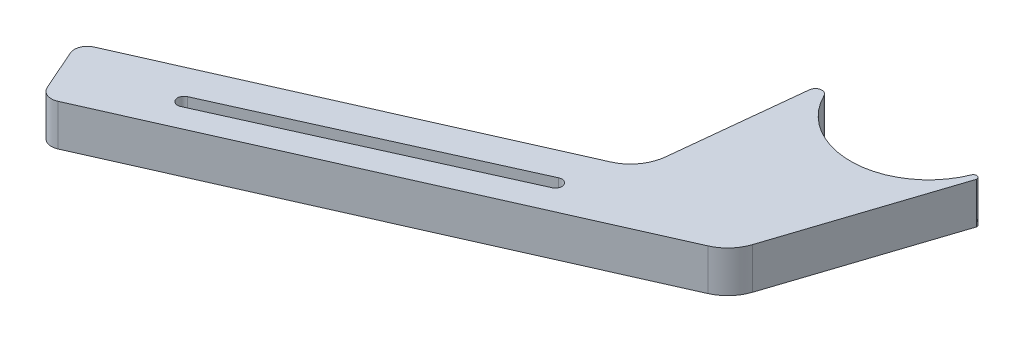
SolidWorks part; units mm, degrees
material "Balsa"
ref_plane "Front Plane" through (0, 0, 0) normal (0, 0, 1) x (1, 0, 0)
ref_plane "Top Plane" through (0, 0, 0) normal (0, 1, 0) x (1, 0, 0)
ref_plane "Right Plane" through (0, 0, 0) normal (1, 0, 0) x (0, 0, -1)
sketch "Sketch1" plane through (0, 0, 0) normal (0, 1, 0) x (1, 0, 0)
  line L0 (-12.6603, -13.6725) -> (-14.7937, -33.7216)
  line L1 (-18.3266, -38.5711) -> (-73.3321, -62.9763)
  line L2 (-74.3491, -65.6155) -> (-71.5345, -71.9592)
  line L5 (12.0828, -12.7648) -> (10.1542, -52.1949) construction
  line L6 (-68.8952, -72.9763) -> (0.304, -42.2735)
  line L7 (12.0828, -12.7648) -> (3.5706, -38.6626)
  line L8 (-59.1472, -63.3168) -> (-19.81, -45.5922) construction
  line L9 (-59.558, -62.4051) -> (-20.2208, -44.6804)
  line L10 (-58.7364, -64.2285) -> (-19.3992, -46.5039)
  arc A0 (11.1201, -12.5524) -> (-10.7686, -13.337) centre (0, -8.0419) cw
  arc A1 (-10.7686, -13.337) -> (-12.6603, -13.6725) centre (-11.6659, -13.7783) ccw
  arc A2 (12.0828, -12.7648) -> (11.1201, -12.5524) centre (11.5834, -12.7403) ccw
  arc A3 (-68.8952, -72.9763) -> (-71.5345, -71.9592) centre (-69.7063, -71.1481) cw
  arc A4 (-74.3491, -65.6155) -> (-73.3321, -62.9763) centre (-72.5209, -64.8044) cw
  arc A5 (3.5706, -38.6626) -> (0.304, -42.2735) centre (-2.1294, -36.7891) cw
  arc A6 (-14.7937, -33.7216) -> (-18.3266, -38.5711) centre (-20.76, -33.0867) cw
  arc A7 (-59.558, -62.4051) -> (-58.7364, -64.2285) centre (-59.1472, -63.3168) ccw
  arc A8 (-19.3992, -46.5039) -> (-20.2208, -44.6804) centre (-19.81, -45.5922) ccw
  point P9 (-11.968, -7.1662)
  point P15 (-70.7233, -73.7874)
  point P18 (-75.1602, -63.7874)
  point P23 (-15.1602, -37.1662)
  point P26 (-39.4786, -54.4545)
  dimension "D1" = 12
  dimension "D2" = 30
  dimension "D5" = 1
  dimension "D6" = 0.5
  dimension "D10" = 2
  dimension "D11" = 6
  dimension "D3" = 120
  dimension "D4" = 10
  dimension "D7" = 60
  dimension "D8" = 90
  dimension "D9" = 90
  dimension "D12" = 1
  dimension "D13" = 0.329
  dimension "D14" = 5
extrude "Boss-Extrude1" add sketch "Sketch1" along normal blind 6.35
